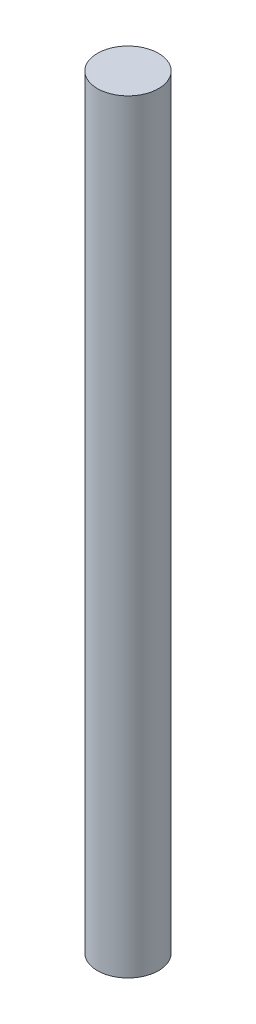
SolidWorks part; units mm, degrees
ref_plane "Спереди" through (0, 0, 0) normal (0, 0, 1) x (1, 0, 0)
ref_plane "Сверху" through (0, 0, 0) normal (0, 1, 0) x (1, 0, 0)
ref_plane "Справа" through (0, 0, 0) normal (1, 0, 0) x (0, 0, -1)
sketch "Эскиз1" plane through (0, 0, 0) normal (0, 1, 0) x (1, 0, 0)
  circle A0 centre (0, 0) radius 4
  dimension "D1" = 8
extrude "Бобышка-Вытянуть1" add sketch "Эскиз1" along normal blind 100
